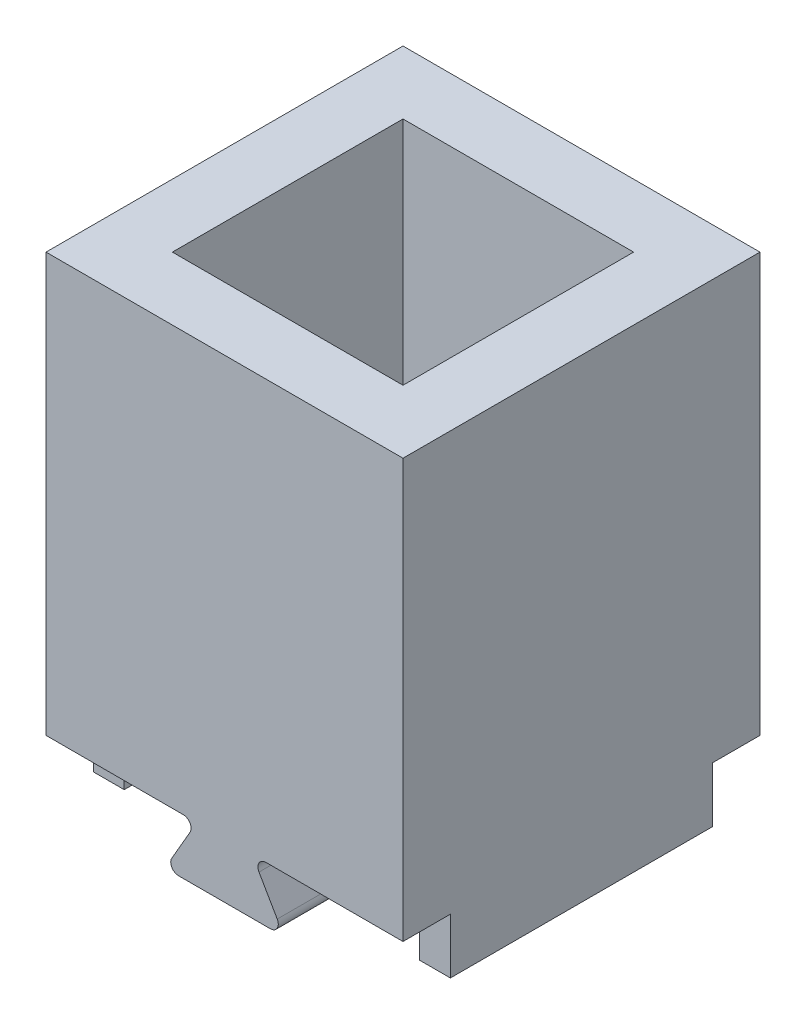
SolidWorks part; units mm, degrees
ref_plane "Front Plane" through (0, 0, 0) normal (0, 0, 1) x (1, 0, 0)
ref_plane "Top Plane" through (0, 0, 0) normal (0, 1, 0) x (1, 0, 0)
ref_plane "Right Plane" through (0, 0, 0) normal (1, 0, 0) x (0, 0, -1)
sketch "Sketch1" plane through (0, 0, 0) normal (0, 1, 0) x (1, 0, 0)
  line L1 (-7.3, -7.3) -> (7.3, -7.3)
  line L2 (-7.3, -7.3) -> (-7.3, 7.3)
  line L3 (-7.3, 7.3) -> (7.3, 7.3)
  line L4 (7.3, -7.3) -> (7.3, 7.3)
  line L5 (-7.3, -7.3) -> (7.3, 7.3) construction
  line L6 (-7.3, 7.3) -> (7.3, -7.3) construction
  line L7 (-11.3, -11.3) -> (11.3, -11.3)
  line L8 (-11.3, -11.3) -> (-11.3, 11.3)
  line L9 (-11.3, 11.3) -> (11.3, 11.3)
  line L10 (11.3, -11.3) -> (11.3, 11.3)
  line L11 (-11.3, -11.3) -> (11.3, 11.3) construction
  line L12 (-11.3, 11.3) -> (11.3, -11.3) construction
  point P0 (0, 0)
  point P6 (0, 0)
  dimension "D1" = 14.6
  dimension "D2" = 22.6
extrude "Boss-Extrude1" add sketch "Sketch1" along normal blind 30
sketch "Sketch2" plane through (0, 0, 11.3) normal (0, 0, 1) x (1, 0, 0)
  line L0 (3.7707, 0) -> (1.75, 3.5)
  line L1 (-11.3, 0) -> (11.3, 0) construction
  line L2 (1.75, 3.5) -> (11.3, 3.5)
  line L3 (11.3, 30) -> (11.3, 0) construction
  line L4 (11.3, 3.5) -> (11.3, 0)
  line L5 (11.3, 0) -> (3.7707, 0)
  line L6 (0, 0) -> (0, 7.2531) construction
  line L7 (-11.3, 3.5) -> (-11.3, 0)
  line L8 (-1.75, 3.5) -> (-11.3, 3.5)
  line L9 (-3.7707, 0) -> (-1.75, 3.5)
  line L10 (-11.3, 0) -> (-3.7707, 0)
  dimension "D1" = 60
  dimension "D2" = 3.5
  dimension "D3" = 1.75
extrude "Cut-Extrude1" cut sketch "Sketch2" against normal through all
fillet "Fillet1" radius 0.5 8 edges at (3.7707, 0, -9.3) (3.7707, 0, 9.3) (-3.7707, 0, -9.3) (-3.7707, 0, 9.3) (1.75, 3.5, -9.3) (1.75, 3.5, 9.3) (-1.75, 3.5, 9.3) (-1.75, 3.5, -9.3)
sketch "Sketch3" plane through (0, 3.5, 0) normal (0, -1, 0) x (-1, 0, 0)
  line L10 (-11.3, 11.3) -> (-11.3, -11.3) construction
  line L11 (-11.3, 8.3) -> (-9.35, 8.3)
  line L12 (-11.3, 8.3) -> (-11.3, -8.3)
  line L13 (-11.3, -8.3) -> (-9.35, -8.3)
  line L14 (-9.35, 8.3) -> (-9.35, -8.3)
  line L15 (11.3, 11.3) -> (11.3, -11.3) construction
  line L16 (9.35, 8.3) -> (11.3, 8.3)
  line L17 (9.35, 8.3) -> (9.35, -8.3)
  line L18 (9.35, -8.3) -> (11.3, -8.3)
  line L19 (11.3, 8.3) -> (11.3, -8.3)
  point P14 (-11.3, 0)
  point P15 (11.3, 0)
  dimension "D1" = 16.6
  dimension "D2" = 1.95
extrude "Boss-Extrude2" add sketch "Sketch3" along normal blind 3.5
